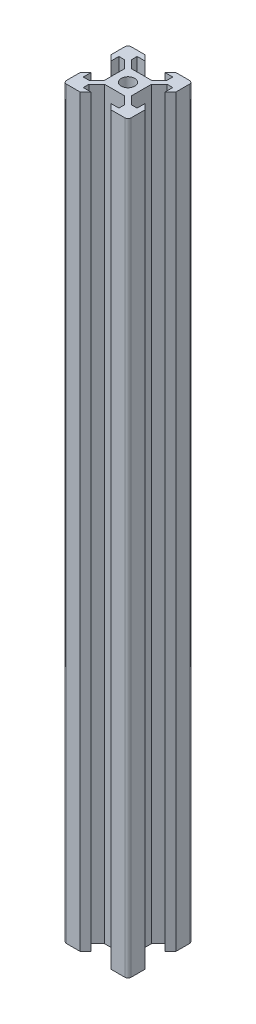
SolidWorks part; units mm, degrees
material "1060 Alloy"
ref_plane "Front Plane" through (0, 0, 0) normal (0, 0, 1) x (1, 0, 0)
ref_plane "Top Plane" through (0, 0, 0) normal (0, 1, 0) x (1, 0, 0)
ref_plane "Right Plane" through (0, 0, 0) normal (1, 0, 0) x (0, 0, -1)
ref_plane "End Plane" through (0, 230, 0) normal (0, 1, 0) x (1, 0, 0)
sketch "MasterLayoutSketch" plane through (0, 0, 0) normal (0, 1, 0) x (1, 0, 0)
  line L0 (-8.325, 3.1) -> (-8.325, 5.5)
  line L1 (-10, -10) -> (10, -10) construction
  line L2 (-10, -10) -> (-10, 10) construction
  line L3 (-10, 10) -> (10, 10) construction
  line L4 (10, -10) -> (10, 10) construction
  line L5 (-10, -10) -> (10, 10) construction
  line L6 (-10, 10) -> (10, -10) construction
  line L7 (-4.775, 10) -> (-3.1, 8.325)
  line L10 (-8.325, 5.5) -> (-6.5607, 5.5)
  line L11 (-10, 4.775) -> (-8.325, 3.1)
  line L12 (-5.5, 8.325) -> (-5.5, 6.5607)
  line L13 (-3.1, 8.325) -> (-5.5, 8.325)
  line L14 (-10, 10) -> (-10, 4.775)
  line L19 (3.1, 8.325) -> (5.5, 8.325)
  line L20 (10, 4.775) -> (8.325, 3.1)
  line L21 (-10, 10) -> (-4.775, 10)
  line L22 (-6.5607, 5.5) -> (-4.1607, 3.1)
  line L23 (-5.5, 6.5607) -> (-3.1, 4.1607)
  line L24 (5.5, 8.325) -> (5.5, 6.5607)
  line L25 (4.775, 10) -> (3.1, 8.325)
  line L26 (8.325, 5.5) -> (6.5607, 5.5)
  line L27 (8.325, 3.1) -> (8.325, 5.5)
  line L28 (10, 10) -> (4.775, 10)
  line L29 (10, 10) -> (10, 4.775)
  line L30 (5.5, 6.5607) -> (3.1, 4.1607)
  line L31 (6.5607, 5.5) -> (4.1607, 3.1)
  line L32 (8.325, -3.1) -> (8.325, -5.5)
  line L33 (4.775, -10) -> (3.1, -8.325)
  line L34 (8.325, -5.5) -> (6.5607, -5.5)
  line L35 (10, -4.775) -> (8.325, -3.1)
  line L36 (5.5, -8.325) -> (5.5, -6.5607)
  line L37 (3.1, -8.325) -> (5.5, -8.325)
  line L38 (10, -10) -> (10, -4.775)
  line L39 (10, -10) -> (4.775, -10)
  line L40 (6.5607, -5.5) -> (4.1607, -3.1)
  line L41 (5.5, -6.5607) -> (3.1, -4.1607)
  line L42 (-3.1, -8.325) -> (-5.5, -8.325)
  line L43 (-10, -4.775) -> (-8.325, -3.1)
  line L44 (-5.5, -8.325) -> (-5.5, -6.5607)
  line L45 (-4.775, -10) -> (-3.1, -8.325)
  line L46 (-8.325, -5.5) -> (-6.5607, -5.5)
  line L47 (-8.325, -3.1) -> (-8.325, -5.5)
  line L48 (-10, -10) -> (-4.775, -10)
  line L49 (-10, -10) -> (-10, -4.775)
  line L50 (-5.5, -6.5607) -> (-3.1, -4.1607)
  line L51 (-6.5607, -5.5) -> (-4.1607, -3.1)
  line L52 (-4.1607, 3.1) -> (-4.1607, -3.1)
  line L53 (-3.1, -4.1607) -> (3.1, -4.1607)
  line L54 (4.1607, -3.1) -> (4.1607, 3.1)
  line L55 (-3.1, 4.1607) -> (3.1, 4.1607)
  circle A0 centre (0, 0) radius 2.1
  point P0 (0, 0)
  point P9 (0, 0)
  dimension "D6" = 4.2
  dimension "D1" = 20
  dimension "D2" = 4
  dimension "D3" = 11
  dimension "D4" = 9.55
  dimension "D5" = 6.2
  dimension "D7" = 1.5
extrude "Main Extrusion" add sketch "MasterLayoutSketch" along normal up to surface (230 mm away) up to plane "End Plane"
fillet "Edge Fillets" radius 1 4 edges at (10, 115, -10) (10, 115, 10) (-10, 115, 10) (-10, 115, -10)
